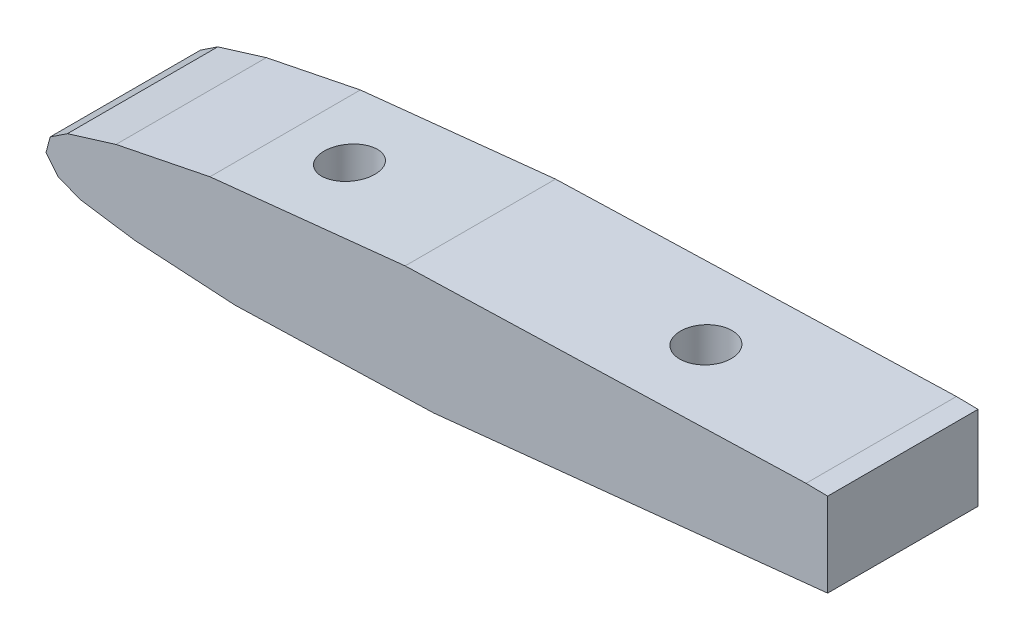
SolidWorks part; units mm, degrees
ref_plane "Front Plane" through (0, 0, 0) normal (0, 0, 1) x (1, 0, 0)
ref_plane "Top Plane" through (0, 0, 0) normal (0, 1, 0) x (1, 0, 0)
ref_plane "Right Plane" through (0, 0, 0) normal (1, 0, 0) x (0, 0, -1)
sketch "Sketch1" plane through (0, 0, 0) normal (0, 0, 1) x (1, 0, 0)
  line B0 (-45.3687, 5.3147) -> (-45.7816, 3.7444)
  line B1 (-43.6487, 6.4548) -> (-45.3687, 5.3147)
  line B2 (-38.7976, 7.9509) -> (-43.6487, 6.4548)
  line B3 (-29.422, 9.8441) -> (-38.7976, 7.9509)
  line B4 (-9.953, 11.879) -> (-29.422, 9.8441)
  line B5 (30.0457, 13.0953) -> (-9.953, 11.879)
  line B6 (81.3103, 12.2432) -> (30.0457, 13.0953)
  line B7 (81.3103, 12.2432) -> (32.1861, 4.678)
  line B8 (32.1861, 4.678) -> (-7.0832, 0.5935)
  line B9 (-7.0832, 0.5935) -> (-26.9187, 0)
  line B10 (-26.9187, 0) -> (-36.9276, 0.597)
  line B11 (-36.9276, 0.597) -> (-42.3647, 1.4051)
  line B12 (-42.3647, 1.4051) -> (-44.5972, 2.2808)
  line B13 (-44.5972, 2.2808) -> (-45.7816, 3.7444)
sketch_block_instance "Part3-1"
sketch_block "Part3"
extrude "Boss-Extrude1" add sketch "Sketch1" along normal blind 15
sketch "Sketch4" plane through (0, 0, 0) normal (0, 1, 0) x (1, 0, 0)
  line L0 (-44.5972, -15) -> (-44.5972, 0) construction
  circle A0 centre (-23.0072, -7.5) radius 2.54
  dimension "D1" = 5.08
  dimension "D2" = 21.59
extrude "Cut-Extrude1" cut sketch "Sketch4" along normal blind 12.7
sketch "Sketch5" plane through (0, 0, 0) normal (0, 1, 0) x (1, 0, 0)
  circle A0 centre (12.5528, -7.5) radius 2.54
  circle A1 centre (-23.0072, -7.5) radius 2.54 construction
  dimension "D1" = 5.08
  dimension "D2" = 35.56
extrude "Cut-Extrude2" cut sketch "Sketch5" along normal blind 15.24
sketch "Sketch6" plane through (0, 0, 0) normal (0, 1, 0) x (1, 0, 0)
  line L1 (32.1966, -15.5121) -> (82.8174, -15.5121)
  line L2 (32.1966, -15.5121) -> (32.1966, 1.2863)
  line L3 (32.1966, 1.2863) -> (82.8174, 1.2863)
  line L4 (82.8174, -15.5121) -> (82.8174, 1.2863)
extrude "Cut-Extrude3" cut sketch "Sketch6" along normal blind 15.24
